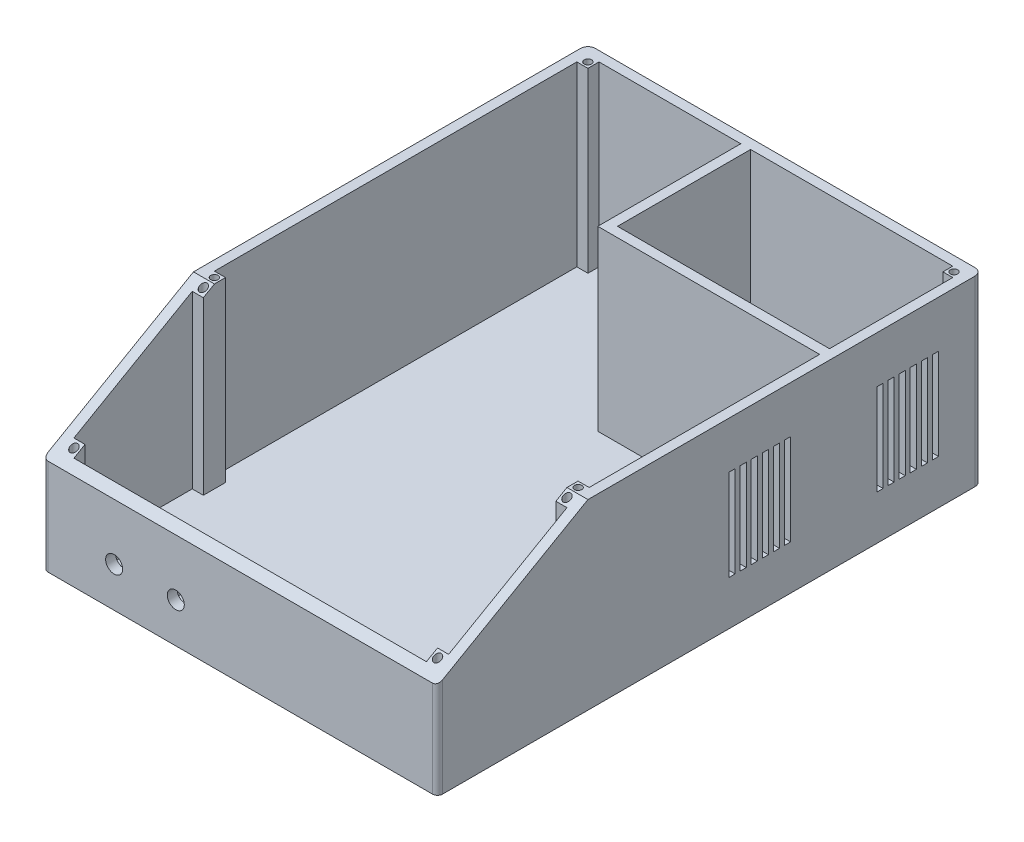
SolidWorks part; units mm, degrees
ref_plane "Front Plane" through (0, 0, 0) normal (0, 0, 1) x (1, 0, 0)
ref_plane "Top Plane" through (0, 0, 0) normal (0, 1, 0) x (1, 0, 0)
ref_plane "Right Plane" through (0, 0, 0) normal (1, 0, 0) x (0, 0, -1)
sketch "Sketch1" plane through (0, 0, 0) normal (0, 1, 0) x (1, 0, 0)
  line L1 (-80, 80) -> (80, 80)
  line L2 (-80, 80) -> (-80, -141)
  line L3 (-80, -141) -> (80, -141)
  line L4 (80, 80) -> (80, -141)
  dimension "D1" = 160
  dimension "D2" = 221
  dimension "D3" = 80
  dimension "D4" = 80
extrude "Boss-Extrude2" add sketch "Sketch1" along normal blind 74
sketch "Sketch7" plane through (80, 0, 0) normal (1, 0, 0) x (0, 0, -1)
  line L0 (-141, 74) -> (-80, 74)
  line L1 (-141, 74) -> (80, 74) construction
  line L2 (-80, 74) -> (-141, 39)
  line L3 (-141, 74) -> (-141, 0) construction
  line L4 (-141, 39) -> (-141, 74)
  dimension "D1" = 61
  dimension "D2" = 35
extrude "Cut-Extrude2" cut sketch "Sketch7" against normal blind 164
sketch "Sketch8" plane through (0, 74, 0) normal (0, 1, 0) x (1, 0, 0)
  line L0 (80, -80) -> (-80, -80) construction
  line L1 (-76, 76) -> (76, 76)
  line L2 (-76, 76) -> (-76, -80)
  line L3 (-76, -80) -> (76, -80)
  line L4 (76, 76) -> (76, -80)
  line L5 (-80, 80) -> (-80, -80) construction
  line L6 (80, -80) -> (80, 80) construction
  line L7 (80, 80) -> (-80, 80) construction
  dimension "D1" = 4
  dimension "D2" = 4
  dimension "D3" = 4
extrude "Cut-Extrude3" cut sketch "Sketch8" against normal blind 72
sketch "Sketch10" plane through (0, 0, 80) normal (0, 0, -1) x (-1, 0, 0)
  line L0 (-80, 74) -> (80, 74) construction
  line L1 (-76, 74) -> (76, 74)
  line L2 (-76, 74) -> (-76, 2)
  line L3 (-76, 2) -> (76, 2)
  line L4 (76, 74) -> (76, 2)
  line L5 (-80, 74) -> (-80, 0) construction
  line L6 (80, 74) -> (80, 0) construction
  line L7 (-80, 0) -> (80, 0) construction
  dimension "D1" = 4
  dimension "D2" = 4
  dimension "D3" = 2
extrude "Cut-Extrude4" cut sketch "Sketch10" against normal blind 57
sketch "Sketch12" plane through (0, 2, 0) normal (0, 1, 0) x (1, 0, 0)
  line L1 (-76, 76) -> (-71.5, 76)
  line L2 (-76, 76) -> (-76, 71.5)
  line L3 (-76, 71.5) -> (-71.5, 71.5)
  line L4 (-71.5, 76) -> (-71.5, 71.5)
  line L5 (76, 76) -> (71.5, 76)
  line L6 (76, 76) -> (76, 71.5)
  line L7 (76, 71.5) -> (71.5, 71.5)
  line L8 (71.5, 76) -> (71.5, 71.5)
  line L9 (-76, -80) -> (-71.5, -80)
  line L10 (-76, -80) -> (-76, -75.5)
  line L11 (-76, -75.5) -> (-71.5, -75.5)
  line L12 (-71.5, -80) -> (-71.5, -75.5)
  line L13 (76, -80) -> (71.5, -80)
  line L14 (76, -80) -> (76, -75.5)
  line L15 (76, -75.5) -> (71.5, -75.5)
  line L16 (71.5, -80) -> (71.5, -75.5)
  point P10 (-71.5, 73.75)
  dimension "D1" = 4.5
  dimension "D2" = 4.5
  dimension "D3" = 4.5
  dimension "D4" = 4.5
  dimension "D5" = 4.5
  dimension "D6" = 4.5
  dimension "D7" = 4.5
  dimension "D8" = 4.5
extrude "Boss-Extrude3" add sketch "Sketch12" along normal blind 72
sketch "Sketch13" plane through (0, 2, 0) normal (0, 1, 0) x (1, 0, 0)
  line L1 (-76, -80) -> (-71.5, -80)
  line L2 (-76, -80) -> (-76, -84.5)
  line L3 (-76, -84.5) -> (-71.5, -84.5)
  line L4 (-71.5, -80) -> (-71.5, -84.5)
  line L5 (-76, -137) -> (-71.5, -137)
  line L6 (-76, -137) -> (-76, -132.5)
  line L7 (-76, -132.5) -> (-71.5, -132.5)
  line L8 (-71.5, -137) -> (-71.5, -132.5)
  line L9 (76, -80) -> (71.5, -80)
  line L10 (76, -80) -> (76, -84.5)
  line L11 (76, -84.5) -> (71.5, -84.5)
  line L12 (71.5, -80) -> (71.5, -84.5)
  line L13 (76, -137) -> (71.5, -137)
  line L14 (76, -137) -> (76, -132.5)
  line L15 (76, -132.5) -> (71.5, -132.5)
  line L16 (71.5, -137) -> (71.5, -132.5)
  point P20 (-73.75, -80)
  point P21 (-76, -134.75)
  dimension "D1" = 4.5
  dimension "D2" = 4.5
  dimension "D3" = 4.5
  dimension "D4" = 4.5
  dimension "D5" = 4.5
  dimension "D6" = 4.5
  dimension "D7" = 4.5
  dimension "D8" = 4.5
extrude "Boss-Extrude4" add sketch "Sketch13" along normal blind 80
sketch "Sketch14" plane through (-76, 0, 0) normal (-1, 0, 0) x (0, 0, 1)
  line L0 (80, 82) -> (84.5, 82)
  line L1 (84.5, 82) -> (84.5, 71.418)
  line L2 (84.5, 71.418) -> (80, 74)
  line L3 (80, 74) -> (80, 82)
  line L4 (137, 41.2951) -> (132.5, 43.877)
  line L5 (141, 39) -> (80, 74) construction
  line L6 (137, 41.2951) -> (132.5, 43.877) construction
  line L7 (132.5, 43.877) -> (132.5, 82)
  line L8 (132.5, 82) -> (137, 82)
  line L9 (137, 82) -> (137, 41.2951)
extrude "Cut-Extrude5" cut sketch "Sketch14" against normal blind 80
sketch "Sketch15" plane through (76, 0, 0) normal (1, 0, 0) x (0, 0, -1)
  line L0 (-137, 41.2951) -> (-132.5, 43.877)
  line L1 (-132.5, 43.877) -> (-132.5, 82)
  line L2 (-132.5, 82) -> (-137, 82)
  line L3 (-137, 82) -> (-137, 41.2951)
  line L4 (-84.5, 71.418) -> (-80, 74)
  line L5 (-80, 74) -> (-80, 82)
  line L6 (-80, 82) -> (-84.5, 82)
  line L7 (-84.5, 82) -> (-84.5, 71.418)
extrude "Cut-Extrude6" cut sketch "Sketch15" against normal blind 80
sketch "Sketch18" plane through (0, 2, 0) normal (0, 1, 0) x (1, 0, 0)
  line L0 (71.5, 76) -> (-71.5, 76) construction
  line L1 (-14, 76) -> (76, 76)
  line L2 (-14, 76) -> (-14, 18)
  line L3 (-14, 18) -> (76, 18)
  line L4 (76, 76) -> (76, 18)
  line L5 (76, -75.5) -> (76, 71.5) construction
  dimension "D1" = 90
  dimension "D2" = 58
extrude "Boss-Extrude6" add sketch "Sketch18" along normal blind 72
sketch "Sketch21" plane through (0, 74, 0) normal (0, 1, 0) x (1, 0, 0)
  line L0 (-14, 76) -> (-14, 18) construction
  line L1 (-10, 76) -> (76, 76)
  line L2 (-10, 76) -> (-10, 22)
  line L3 (-10, 22) -> (76, 22)
  line L4 (76, 76) -> (76, 22)
  line L6 (-14, 18) -> (76, 18) construction
  line L7 (80, -80) -> (80, 80) construction
  line L8 (80, 80) -> (-80, 80) construction
  dimension "D1" = 4
  dimension "D2" = 4
  dimension "D3" = 4
  dimension "D4" = 4
extrude "Cut-Extrude7" cut sketch "Sketch21" against normal blind 72
sketch "Sketch22" plane through (0, 2, 0) normal (0, 1, 0) x (1, 0, 0)
  line L1 (76, 76) -> (72, 76)
  line L2 (76, 76) -> (76, 72)
  line L3 (76, 72) -> (72, 72)
  line L4 (72, 76) -> (72, 72)
  point P5 (76, 74)
  dimension "D1" = 4
  dimension "D2" = 4
extrude "Boss-Extrude7" add sketch "Sketch22" along normal blind 72
sketch "Sketch24" plane through (-14, 0, 0) normal (-1, 0, 0) x (0, 0, 1)
  circle A0 centre (-68.2054, 13.1987) radius 2.25
  circle A1 centre (-68.2054, 20.1987) radius 2.25
  dimension "D2" = 4.5
  dimension "D3" = 4.5
  dimension "D1" = 7
extrude "Cut-Extrude8" cut sketch "Sketch24" against normal blind 5.9
sketch "Sketch25" plane through (0, 2, 0) normal (0, 1, 0) x (1, 0, 0)
  line L0 (-10, 76) -> (-10, 22) construction
  line L1 (3, 51) -> (65.3, 51)
  line L2 (3, 51) -> (3, 30.9)
  line L3 (3, 30.9) -> (65.3, 30.9)
  line L4 (65.3, 51) -> (65.3, 30.9)
  line L5 (72, 76) -> (-10, 76) construction
  dimension "D1" = 62.3
  dimension "20.1" = 20.1
  dimension "D3" = 13
  dimension "D4" = 25
extrude "Boss-Extrude8" add sketch "Sketch25" along normal blind 16.5
fillet "Fillet1" radius 3 1 edges at (80, 37, -80)
fillet "Fillet2" radius 3 1 edges at (-80, 37, -80)
fillet "Fillet3" radius 2 1 edges at (80, 19.5, 141)
fillet "Fillet4" radius 2 1 edges at (-80, 19.5, 141)
sketch "Sketch28" plane through (0, 2, 0) normal (0, 1, 0) x (1, 0, 0)
  line L0 (71.5, -137) -> (-71.5, -137) construction
  line L1 (-60.99, -126.46) -> (-41.18, -126.46)
  line L2 (-60.99, -126.46) -> (-60.99, -137)
  line L3 (-60.99, -137) -> (-41.18, -137)
  line L4 (-41.18, -126.46) -> (-41.18, -137)
  line L5 (-76, -84.5) -> (-76, -132.5) construction
  line L6 (-35.99, -126.46) -> (-35.99, -137)
  line L7 (-35.99, -126.46) -> (-16.18, -126.46)
  line L8 (-16.18, -126.46) -> (-16.18, -137)
  line L9 (-35.99, -137) -> (-16.18, -137)
  dimension "D1" = 19.81
  dimension "D2" = 10.54
  dimension "D3" = 15.01
  dimension "D4" = 2
extrude "Boss-Extrude10" add sketch "Sketch28" along normal blind 6.35
sketch "Sketch29" plane through (0, 2, 0) normal (0, 1, 0) x (1, 0, 0)
  line L0 (-71.5, -137) -> (71.5, -137) construction
  line L1 (-62.39, -126.46) -> (-59.89, -126.46)
  line L2 (-62.39, -126.46) -> (-62.39, -137)
  line L3 (-62.39, -137) -> (-59.89, -137)
  line L4 (-59.89, -126.46) -> (-59.89, -137)
  line L5 (-60.99, -126.46) -> (-60.99, -137) construction
  line L6 (-41.18, -126.46) -> (-60.99, -126.46) construction
  line L7 (-42.28, -126.46) -> (-39.78, -126.46)
  line L8 (-42.28, -126.46) -> (-42.28, -137)
  line L9 (-42.28, -137) -> (-39.78, -137)
  line L10 (-39.78, -126.46) -> (-39.78, -137)
  line L20 (-16.18, -126.46) -> (-35.99, -126.46) construction
  line L21 (-37.39, -126.46) -> (-34.89, -126.46)
  line L22 (-37.39, -126.46) -> (-37.39, -137)
  line L23 (-37.39, -137) -> (-34.89, -137)
  line L24 (-34.89, -126.46) -> (-34.89, -137)
  line L25 (-17.28, -126.46) -> (-14.782, -126.46)
  line L26 (-17.28, -126.46) -> (-17.28, -137)
  line L27 (-17.28, -137) -> (-14.782, -137)
  line L28 (-14.782, -126.46) -> (-14.782, -137)
  dimension "D1" = 10.54
  dimension "D2" = 2.5
  dimension "D3" = 1.1
  dimension "D4" = 2.5
  dimension "D5" = 1.1
  dimension "D6" = 10.54
  dimension "D8" = 1.1
  dimension "D9" = 2.498
  dimension "D10" = 1.1
  dimension "D7" = 2.5
extrude "Boss-Extrude11" add sketch "Sketch29" along normal blind 22.35
sketch "Sketch33" plane through (0, 0, 137) normal (0, 0, -1) x (-1, 0, 0)
  circle A0 centre (51.1876, 16.1787) radius 3.45
  circle A1 centre (26.1876, 16.1787) radius 3.45
  dimension "D2" = 6.9
  dimension "D1" = 25
  dimension "D3" = 2
extrude "Cut-Extrude11" cut sketch "Sketch33" against normal blind 22.35
sketch "Sketch34" plane through (0, 0, -76) normal (0, 0, 1) x (1, 0, 0)
  line L0 (77, 0) -> (-77, 0) construction
  line L1 (32.1, 24.9) -> (59.5, 24.9)
  line L2 (32.1, 24.9) -> (32.1, 5.5)
  line L3 (32.1, 5.5) -> (59.5, 5.5)
  line L4 (59.5, 24.9) -> (59.5, 5.5)
  line L5 (77, 74) -> (77, 0) construction
  line L8 (-78, 0) -> (78, 0) construction
  circle A0 centre (64.8, 15.4641) radius 1.55
  circle A1 centre (26.8, 15.4) radius 1.55
  point P14 (0, 0)
  dimension "D7" = 3.1
  dimension "3" = 3.1
  dimension "D1" = 27.4
  dimension "D2" = 19.4
  dimension "D3" = 5.5
  dimension "D4" = 17.5
  dimension "D5" = 5.3
  dimension "D6" = 9.9
  dimension "D8" = 38
  dimension "D9" = 15.4641
extrude "Cut-Extrude12" cut sketch "Sketch34" against normal blind 10
sketch "Sketch44" plane through (0, 74, 0) normal (0, 1, 0) x (1, 0, 0)
  line L1 (-76, 71.5) -> (-71.5, 71.5) construction
  line L2 (-71.5, 71.5) -> (-71.5, 76) construction
  circle A0 centre (-73.75, 73.75) radius 1.5
  dimension "D1" = 3
  dimension "D2" = 2.25
  dimension "D3" = 2.25
extrude "Cut-Extrude13" cut sketch "Sketch44" against normal blind 52
sketch "Sketch47" plane through (0, 74, 0) normal (0, 1, 0) x (1, 0, 0)
  line L0 (72, 72) -> (76, 72) construction
  line L5 (72, 76) -> (72, 72) construction
  circle A0 centre (74.25, 74.25) radius 1.5
  point P2 (74, 72)
  dimension "D3" = 3
  dimension "D1" = 2.25
  dimension "D2" = 2.25
extrude "Cut-Extrude15" cut sketch "Sketch47" against normal blind 52
sketch "Sketch48" plane through (0, 74, 0) normal (0, 1, 0) x (1, 0, 0)
  line L0 (71.5, -75.5) -> (71.5, -84.5) construction
  line L1 (76, -75.5) -> (71.5, -75.5) construction
  circle A0 centre (73.75, -77.75) radius 1.5
  dimension "D1" = 3
  dimension "D2" = 2.25
  dimension "D3" = 2.25
extrude "Cut-Extrude16" cut sketch "Sketch48" against normal blind 52
sketch "Sketch52" plane through (0, 2, 0) normal (0, 1, 0) x (1, 0, 0)
  line L0 (71.5, -84.5) -> (71.5, -80) construction
  line L1 (71.5, -84.5) -> (76, -84.5) construction
  line L2 (-71.5, -84.5) -> (-71.5, -75.5) construction
  line L3 (-71.5, -84.5) -> (-76, -84.5) construction
  line L4 (-71.5, -132.5) -> (-76, -132.5) construction
  line L5 (-71.5, -137) -> (-71.5, -132.5) construction
  line L6 (76, -132.5) -> (71.5, -132.5) construction
  line L7 (71.5, -132.5) -> (71.5, -137) construction
  circle A0 centre (73.75, -82.25) radius 1.5
  circle A1 centre (-73.75, -82.25) radius 1.5
  circle A2 centre (-73.75, -134.75) radius 1.5
  circle A3 centre (73.75, -134.75) radius 1.5
  dimension "D1" = 3
  dimension "D2" = 2.25
  dimension "D4" = 3
  dimension "D7" = 3
  dimension "D10" = 3
  dimension "D3" = 2.25
  dimension "D5" = 2.25
  dimension "D6" = 2.25
  dimension "D8" = 2.25
  dimension "D9" = 2.25
  dimension "D11" = 2.25
  dimension "D12" = 2.25
extrude "Cut-Extrude19" cut sketch "Sketch52" along normal blind 69 from offset 15
sketch "Sketch54" plane through (0, 74, 0) normal (0, 1, 0) x (1, 0, 0)
  line L0 (-71.5, -80) -> (-80, -80) construction
  line L1 (-71.5, -80) -> (-71.5, -75.5) construction
  circle A0 centre (-73.75, -77.75) radius 1.5
  dimension "D1" = 3
  dimension "D2" = 2.25
  dimension "D3" = 2.25
extrude "Cut-Extrude20" cut sketch "Sketch54" against normal blind 52
sketch "Sketch65" plane through (0, 0, -76) normal (0, 0, 1) x (1, 0, 0)
  line L0 (-14, 2) -> (76, 2) construction
  circle A0 centre (26.8591, 15.2312) radius 3.15
  circle A1 centre (64.7991, 15.2312) radius 3.15
  dimension "D1" = 6.3
  dimension "D2" = 13.2312
  dimension "D4" = 37.94
  dimension "D3" = 2
extrude "Boss-Extrude16" add sketch "Sketch65" along normal blind 10
sketch "Sketch66" plane through (0, 0, -76) normal (0, 0, 1) x (1, 0, 0)
  line L0 (77, 0) -> (-77, 0) construction
  line L1 (32.1, 24.9) -> (32.1, 5.5) construction
  circle A0 centre (26.8405, 15.2774) radius 1.5
  point P2 (0, 0)
  dimension "D1" = 3
  dimension "D3" = 5.2595
  dimension "D2" = 15.2774
extrude "Cut-Extrude24" cut sketch "Sketch66" along normal blind 15
sketch "Sketch67" plane through (0, 0, -76) normal (0, 0, 1) x (1, 0, 0)
  line L0 (77, 0) -> (-77, 0) construction
  line L1 (59.5, 5.5) -> (59.5, 24.9) construction
  circle A0 centre (64.9523, 15.4) radius 1.5
  dimension "D1" = 3
  dimension "D2" = 15.4
  dimension "D3" = 5.4523
extrude "Cut-Extrude25" cut sketch "Sketch67" along normal blind 15
sketch "Sketch68" plane through (80, 0, 0) normal (1, 0, 0) x (0, 0, -1)
  line L0 (-22.767, 55.0174) -> (-22.767, 18.0174)
  line L1 (37.233, 55.0174) -> (62.233, 55.0174)
  line L2 (37.233, 55.0174) -> (37.233, 18.0174)
  line L3 (37.233, 18.0174) -> (62.233, 18.0174)
  line L4 (62.233, 55.0174) -> (62.233, 18.0174)
  line L5 (-22.767, 55.0174) -> (2.233, 55.0174)
  line L6 (2.233, 55.0174) -> (2.233, 18.0174)
  line L7 (-22.767, 18.0174) -> (2.233, 18.0174)
  dimension "D1" = 25
  dimension "D2" = 37
  dimension "D3" = 2
extrude "Cut-Extrude26" cut sketch "Sketch68" against normal blind 15
sketch "Sketch69" plane through (80, 0, 0) normal (1, 0, 0) x (0, 0, -1)
  line L0 (62.233, 55.0174) -> (37.233, 55.0174) construction
  line L1 (39.733, 55.0174) -> (41.733, 55.0174)
  line L2 (39.733, 55.0174) -> (39.733, 18.0174)
  line L3 (39.733, 18.0174) -> (41.733, 18.0174)
  line L4 (41.733, 55.0174) -> (41.733, 18.0174)
  line L5 (37.233, 55.0174) -> (37.233, 18.0174) construction
  line L6 (44.233, 55.0174) -> (44.233, 18.0174)
  line L7 (44.233, 55.0174) -> (46.233, 55.0174)
  line L8 (46.233, 55.0174) -> (46.233, 18.0174)
  line L9 (44.233, 18.0174) -> (46.233, 18.0174)
  line L10 (48.733, 55.0174) -> (48.733, 18.0174)
  line L11 (48.733, 55.0174) -> (50.733, 55.0174)
  line L12 (50.733, 55.0174) -> (50.733, 18.0174)
  line L13 (48.733, 18.0174) -> (50.733, 18.0174)
  line L14 (53.233, 55.0174) -> (53.233, 18.0174)
  line L15 (53.233, 55.0174) -> (55.233, 55.0174)
  line L16 (55.233, 55.0174) -> (55.233, 18.0174)
  line L17 (53.233, 18.0174) -> (55.233, 18.0174)
  line L18 (57.733, 55.0174) -> (57.733, 18.0174)
  line L19 (57.733, 18.0174) -> (59.733, 18.0174)
  line L20 (59.733, 55.0174) -> (59.733, 18.0174)
  line L21 (57.733, 55.0174) -> (59.733, 55.0174)
  line L22 (-20.267, 55.0174) -> (-20.267, 18.0174)
  line L23 (-20.267, 55.0174) -> (-18.267, 55.0174)
  line L24 (-18.267, 55.0174) -> (-18.267, 18.0174)
  line L25 (-20.267, 18.0174) -> (-18.267, 18.0174)
  line L26 (-15.767, 55.0174) -> (-15.767, 18.0174)
  line L27 (-15.767, 18.0174) -> (-13.767, 18.0174)
  line L28 (-13.767, 55.0174) -> (-13.767, 18.0174)
  line L29 (-15.767, 55.0174) -> (-13.767, 55.0174)
  line L30 (-11.267, 55.0174) -> (-11.267, 18.0174)
  line L31 (-11.267, 18.0174) -> (-9.267, 18.0174)
  line L32 (-9.267, 55.0174) -> (-9.267, 18.0174)
  line L33 (-11.267, 55.0174) -> (-9.267, 55.0174)
  line L34 (-6.767, 55.0174) -> (-6.767, 18.0174)
  line L35 (-6.767, 18.0174) -> (-4.767, 18.0174)
  line L36 (-4.767, 55.0174) -> (-4.767, 18.0174)
  line L37 (-6.767, 55.0174) -> (-4.767, 55.0174)
  line L38 (-2.267, 55.0174) -> (-2.267, 18.0174)
  line L39 (-2.267, 18.0174) -> (-0.267, 18.0174)
  line L40 (-0.267, 55.0174) -> (-0.267, 18.0174)
  line L41 (-2.267, 55.0174) -> (-0.267, 55.0174)
  point P46 (0, 0)
  dimension "D1" = 37
  dimension "D2" = 2.5
  dimension "D3" = 2
  dimension "D5" = 2.5
  dimension "D6" = 2
  dimension "D7" = 2.5
  dimension "D8" = 2
  dimension "D10" = 2.5
  dimension "D11" = 2.5
  dimension "D4" = 4
  dimension "D9" = 5
extrude "Boss-Extrude18" add sketch "Sketch69" against normal blind 4
sketch "Sketch70" plane through (0, 74, 0) normal (0, 1, 0) x (1, 0, 0)
  line L4 (72, 72) -> (76, 72)
equation "\"2.5.00mm\"=5"
